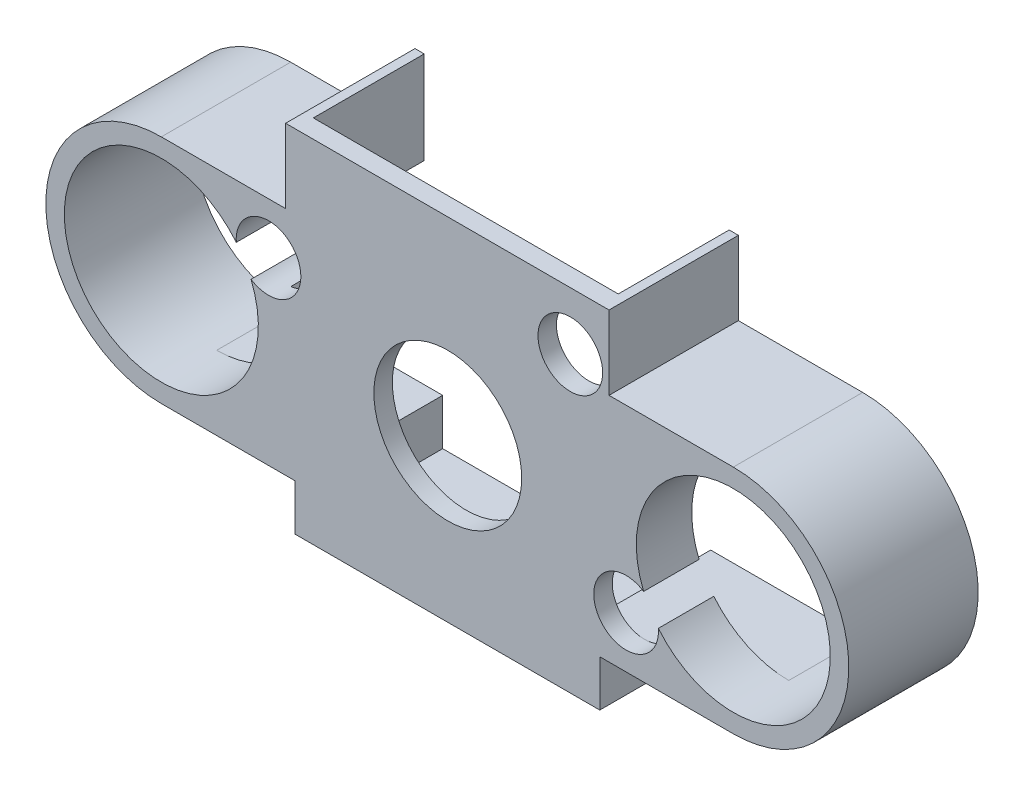
SolidWorks part; units mm, degrees
ref_plane "Front Plane" through (0, 0, 0) normal (0, 0, 1) x (1, 0, 0)
ref_plane "Top Plane" through (0, 0, 0) normal (0, 1, 0) x (1, 0, 0)
ref_plane "Right Plane" through (0, 0, 0) normal (1, 0, 0) x (0, 0, -1)
ref_plane "Plane_FrontFace" through (0, 0, 3) normal (0, 0, 1) x (1, 0, 0)
sketch "Sk_FrontPlate" plane through (0, 0, 3) normal (0, 0, 1) x (1, 0, 0)
  line L0 (29.79, 18) -> (16.34, 18)
  line L1 (16.34, 18) -> (16.34, 26)
  line L2 (16.34, 26) -> (-18.66, 26)
  line L3 (-18.66, 26) -> (-18.66, 18)
  line L4 (-18.66, 18) -> (-32.11, 18)
  line L5 (-32.11, -7) -> (-17.66, -7)
  line L6 (-17.66, -7) -> (-17.66, -12)
  line L7 (-17.66, -12) -> (15.34, -12)
  line L8 (15.34, -12) -> (15.34, -7)
  line L9 (15.34, -7) -> (29.79, -7)
  arc A0 (29.79, -7) -> (29.79, 18) centre (29.79, 5.5) ccw
  arc A1 (-32.11, 18) -> (-32.11, -7) centre (-32.11, 5.5) ccw
extrude "Front Plate" add sketch "Sk_FrontPlate" against normal blind 2
ref_plane "Plane_PlateBack" through (0, 0, 1) normal (0, 0, 1) x (1, 0, 0)
sketch "Sk_ShellOuter" plane through (0, 0, 1) normal (0, 0, 1) x (1, 0, 0)
  line L0 (29.79, 18) -> (16.34, 18)
  line L1 (16.34, 18) -> (16.34, 26)
  line L2 (16.34, 26) -> (-18.66, 26)
  line L3 (-18.66, 26) -> (-18.66, 18)
  line L4 (-18.66, 18) -> (-32.11, 18)
  line L5 (-32.11, -7) -> (-17.66, -7)
  line L6 (-17.66, -7) -> (-17.66, -12)
  line L7 (-17.66, -12) -> (15.34, -12)
  line L8 (15.34, -12) -> (15.34, -7)
  line L9 (15.34, -7) -> (29.79, -7)
  arc A0 (29.79, -7) -> (29.79, 18) centre (29.79, 5.5) ccw
  arc A1 (-32.11, 18) -> (-32.11, -7) centre (-32.11, 5.5) ccw
extrude "Shell" add sketch "Sk_ShellOuter" against normal blind 12
sketch "Sk_ShellInner" plane through (0, 0, 1) normal (0, 0, 1) x (1, 0, 0)
  line L0 (29.79, 16) -> (15.34, 16)
  line L1 (15.34, 16) -> (15.34, 27)
  line L2 (15.34, 27) -> (-17.66, 27)
  line L3 (-17.66, 27) -> (-17.66, 16)
  line L4 (-17.66, 16) -> (-32.11, 16)
  line L5 (-32.11, -5) -> (-15.66, -5)
  line L6 (-15.66, -5) -> (-15.66, -10)
  line L7 (-15.66, -10) -> (13.34, -10)
  line L8 (13.34, -10) -> (13.34, -5)
  line L9 (13.34, -5) -> (29.79, -5)
  arc A0 (29.79, -5) -> (29.79, 16) centre (29.79, 5.5) ccw
  arc A1 (-32.11, 16) -> (-32.11, -5) centre (-32.11, 5.5) ccw
extrude "Shell Hollow" cut sketch "Sk_ShellInner" against normal blind 12
sketch "Sk_IRRings" plane through (0, 0, 1) normal (0, 0, 1) x (1, 0, 0)
  circle A0 centre (-32.11, 5.5) radius 12.5
  circle A1 centre (-32.11, 5.5) radius 10.5
  circle A2 centre (29.79, 5.5) radius 12.5
  circle A3 centre (29.79, 5.5) radius 10.5
extrude "IR LED Rings" add sketch "Sk_IRRings" against normal blind 4
sketch "Sk_FrontOpenings" plane through (0, 0, 0) normal (0, 0, 1) x (1, 0, 0)
  circle A0 centre (-1.11, 5.5) radius 8
  circle A1 centre (12.15, 19.76) radius 3.5
  circle A2 centre (-32.11, 5.5) radius 10.5
  circle A3 centre (29.79, 5.5) radius 10.5
extrude "Lens, LDR and IR Openings" cut sketch "Sk_FrontOpenings" against normal through all and the other way through all
sketch "Sk_IRNotches" plane through (0, 0, 0) normal (0, 0, 1) x (1, 0, 0)
  circle A0 centre (-20.51, 12.45) radius 3.5
  circle A1 centre (18.19, -1.45) radius 3.5
extrude "IR Board Notches" cut sketch "Sk_IRNotches" against normal through all and the other way through all
